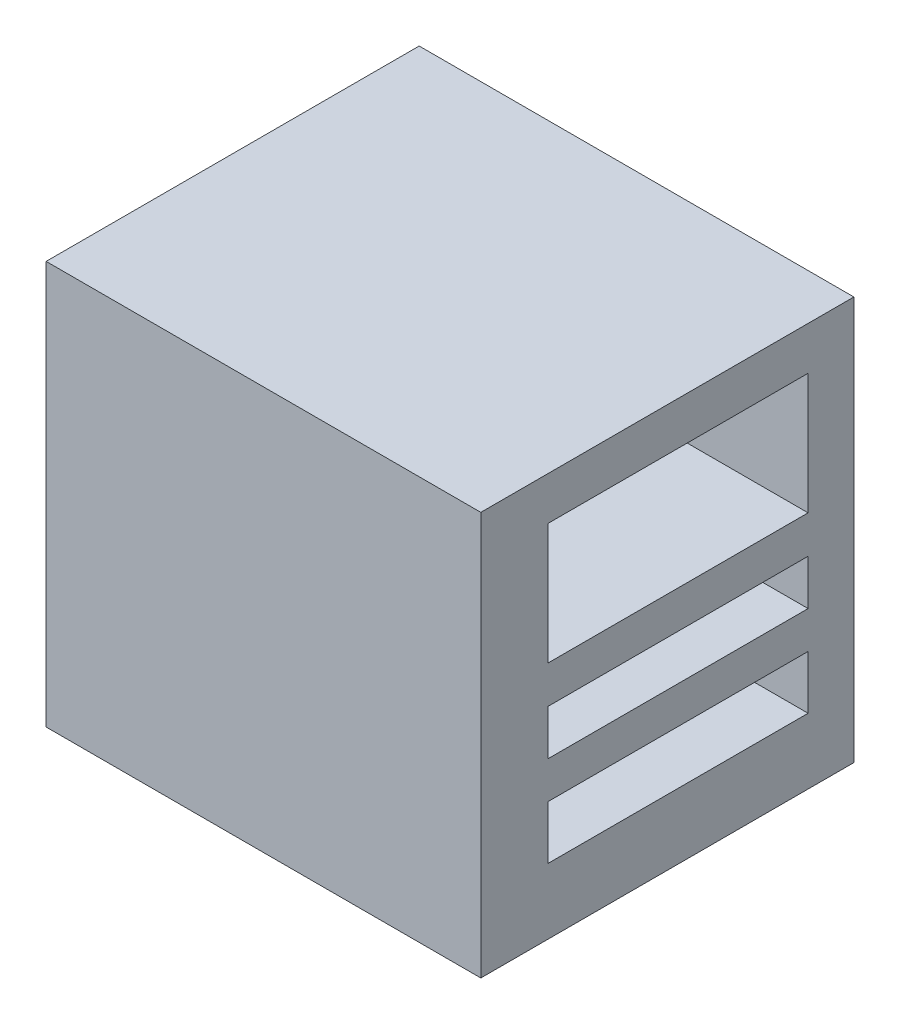
SolidWorks part; units mm, degrees
ref_plane "Front Plane" through (0, 0, 0) normal (0, 0, 1) x (1, 0, 0)
ref_plane "Top Plane" through (0, 0, 0) normal (0, 1, 0) x (1, 0, 0)
ref_plane "Right Plane" through (0, 0, 0) normal (1, 0, 0) x (0, 0, -1)
sketch "Sketch1" plane through (0, 0, 0) normal (1, 0, 0) x (0, 0, -1)
  line L1 (-40.1282, 35.8571) -> (45.6905, 35.8571)
  line L2 (-40.1282, 35.8571) -> (-40.1282, -56.9145)
  line L3 (-40.1282, -56.9145) -> (45.6905, -56.9145)
  line L4 (45.6905, 35.8571) -> (45.6905, -56.9145)
  line L5 (-24.6331, 25.9244) -> (35.1618, 25.9244)
  line L6 (-24.6331, 25.9244) -> (-24.6331, -1.8872)
  line L7 (-24.6331, -1.8872) -> (35.1618, -1.8872)
  line L8 (35.1618, 25.9244) -> (35.1618, -1.8872)
  line L9 (-24.6331, -10.5287) -> (35.1618, -10.5287)
  line L10 (-24.6331, -10.5287) -> (-24.6331, -20.958)
  line L11 (-24.6331, -20.958) -> (35.1618, -20.958)
  line L12 (35.1618, -10.5287) -> (35.1618, -20.958)
  line L13 (-24.6331, -29.5002) -> (35.1618, -29.5002)
  line L14 (-24.6331, -29.5002) -> (-24.6331, -41.8167)
  line L15 (-24.6331, -41.8167) -> (35.1618, -41.8167)
  line L16 (35.1618, -29.5002) -> (35.1618, -41.8167)
extrude "Boss-Extrude1" add sketch "Sketch1" along normal blind 100
